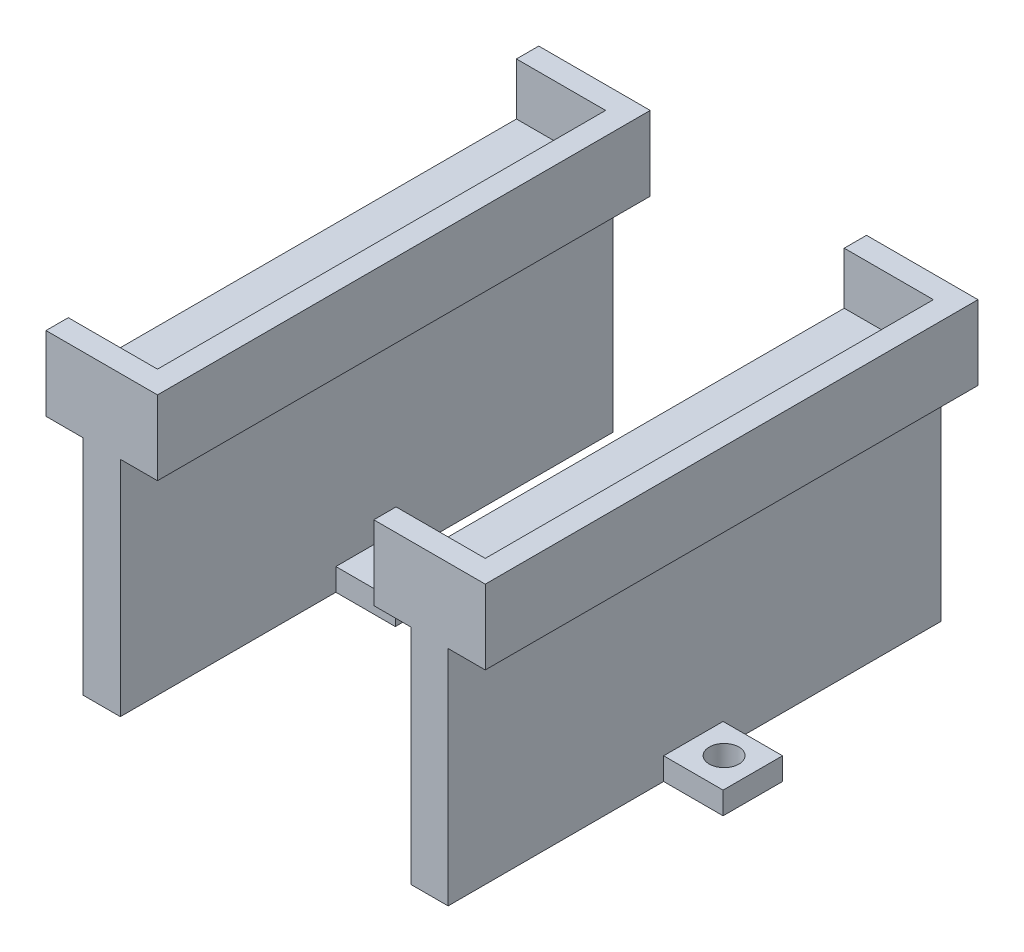
SolidWorks part; units mm, degrees
ref_plane "Front Plane" through (0, 0, 0) normal (0, 0, 1) x (1, 0, 0)
ref_plane "Top Plane" through (0, 0, 0) normal (0, 1, 0) x (1, 0, 0)
ref_plane "Right Plane" through (0, 0, 0) normal (1, 0, 0) x (0, 0, -1)
sketch "Sketch1" plane through (0, 0, 0) normal (0, 1, 0) x (1, 0, 0)
  line L1 (64.0039, -39.1135) -> (-112.9961, -39.1135)
  line L2 (64.0039, -39.1135) -> (64.0039, 27.1865)
  line L3 (64.0039, 27.1865) -> (-112.9961, 27.1865)
  line L4 (-112.9961, -39.1135) -> (-112.9961, 27.1865)
  line L5 (64.0039, -39.1135) -> (-112.9961, 27.1865) construction
  line L6 (64.0039, 27.1865) -> (-112.9961, -39.1135) construction
  point P0 (-24.4961, -5.9635)
  point P5 (0, 0.6131)
extrude "Boss-Extrude1" add sketch "Sketch1" along normal blind 10
sketch "Sketch2" plane through (0, 10, 0) normal (0, 1, 0) x (1, 0, 0)
  line L0 (-112.9961, -39.1135) -> (64.0039, -39.1135) construction
  line L1 (61.0039, -36.1135) -> (-109.9961, -36.1135)
  line L2 (61.0039, -36.1135) -> (61.0039, 24.1865)
  line L3 (61.0039, 24.1865) -> (-109.9961, 24.1865)
  line L4 (-109.9961, -36.1135) -> (-109.9961, 24.1865)
  line L5 (61.0039, -36.1135) -> (-109.9961, 24.1865) construction
  line L6 (61.0039, 24.1865) -> (-109.9961, -36.1135) construction
  line L7 (64.0039, -39.1135) -> (64.0039, 27.1865) construction
  point P0 (-24.4961, -5.9635)
  dimension "D1" = 3
  dimension "D2" = 3
extrude "Cut-Extrude1" cut sketch "Sketch2" against normal blind 7 and the other way through all
sketch "Sketch3" plane through (0, 0, 0) normal (0, -1, 0) x (1, 0, 0)
  line L0 (-112.9961, 39.1135) -> (64.0039, 39.1135) construction
  line L1 (-107.9961, 39.1135) -> (-102.9961, 39.1135)
  line L2 (-107.9961, 39.1135) -> (-107.9961, -27.1865)
  line L3 (-107.9961, -27.1865) -> (-102.9961, -27.1865)
  line L4 (-102.9961, 39.1135) -> (-102.9961, -27.1865)
  line L5 (-107.9961, 39.1135) -> (-102.9961, -27.1865) construction
  line L6 (-107.9961, -27.1865) -> (-102.9961, 39.1135) construction
  line L7 (54.0039, 39.1135) -> (59.0039, 39.1135)
  line L8 (54.0039, 39.1135) -> (54.0039, -27.1865)
  line L9 (54.0039, -27.1865) -> (59.0039, -27.1865)
  line L10 (59.0039, 39.1135) -> (59.0039, -27.1865)
  line L11 (54.0039, 39.1135) -> (59.0039, -27.1865) construction
  line L12 (54.0039, -27.1865) -> (59.0039, 39.1135) construction
  line L13 (64.0039, -27.1865) -> (-112.9961, -27.1865) construction
  line L14 (-112.9961, -27.1865) -> (-112.9961, 39.1135) construction
  line L15 (64.0039, 39.1135) -> (64.0039, -27.1865) construction
  point P0 (-105.4961, 5.9635)
  point P5 (56.5039, 5.9635)
  dimension "D1" = 0
  dimension "D2" = 0
  dimension "D3" = 0
  dimension "D4" = 0
  dimension "D5" = 5
  dimension "D6" = 5
  dimension "D7" = 5
extrude "Boss-Extrude2" add sketch "Sketch3" along normal blind 30
sketch "Sketch4" plane through (0, 0, 0) normal (0, -1, 0) x (1, 0, 0)
  line L0 (-102.9961, 39.1135) -> (54.0039, 39.1135) construction
  line L1 (49.0039, -27.1865) -> (-97.9961, -27.1865)
  line L2 (49.0039, -27.1865) -> (49.0039, 39.1135)
  line L3 (49.0039, 39.1135) -> (-97.9961, 39.1135)
  line L4 (-97.9961, -27.1865) -> (-97.9961, 39.1135)
  line L5 (49.0039, -27.1865) -> (-97.9961, 39.1135) construction
  line L6 (49.0039, 39.1135) -> (-97.9961, -27.1865) construction
  line L7 (54.0039, -27.1865) -> (-102.9961, -27.1865) construction
  line L8 (-102.9961, -27.1865) -> (-102.9961, 39.1135) construction
  line L9 (54.0039, 39.1135) -> (54.0039, -27.1865) construction
  point P0 (-24.4961, 5.9635)
  dimension "D1" = 0
  dimension "D2" = 0
  dimension "D3" = 5
  dimension "D4" = 5
extrude "Cut-Extrude2" cut sketch "Sketch4" against normal blind 30
sketch "Sketch5" plane through (0, -30, 0) normal (0, -1, 0) x (1, 0, 0)
  line L0 (-107.9961, 39.1135) -> (-107.9961, -27.1865) construction
  line L1 (-107.9961, 2.1135) -> (-115.9961, 2.1135)
  line L2 (-107.9961, 2.1135) -> (-107.9961, 10.1135)
  line L3 (-107.9961, 10.1135) -> (-115.9961, 10.1135)
  line L4 (-115.9961, 2.1135) -> (-115.9961, 10.1135)
  line L5 (-107.9961, 2.1135) -> (-115.9961, 10.1135) construction
  line L6 (-107.9961, 10.1135) -> (-115.9961, 2.1135) construction
  line L7 (67.0039, 2.1135) -> (59.0039, 2.1135)
  line L8 (67.0039, 2.1135) -> (67.0039, 10.1135)
  line L9 (67.0039, 10.1135) -> (59.0039, 10.1135)
  line L10 (59.0039, 2.1135) -> (59.0039, 10.1135)
  line L11 (67.0039, 2.1135) -> (59.0039, 10.1135) construction
  line L12 (67.0039, 10.1135) -> (59.0039, 2.1135) construction
  line L13 (59.0039, -27.1865) -> (59.0039, 39.1135) construction
  line L14 (-112.9961, 39.1135) -> (-107.9961, 39.1135) construction
  line L15 (59.0039, 39.1135) -> (64.0039, 39.1135) construction
  circle A0 centre (-111.977, 5.9964) radius 1.8999
  circle A1 centre (63.046, 6.0212) radius 1.9942
  point P0 (-111.9961, 6.1135)
  point P5 (63.0039, 6.1135)
  dimension "D1" = 0
  dimension "D2" = 0
  dimension "D3" = 29
  dimension "D4" = 29
  dimension "D5" = 4
  dimension "D6" = 4
extrude "Boss-Extrude3" add sketch "Sketch5" against normal blind 3
sketch "Sketch6" plane through (0, 0, -27.1865) normal (0, 0, -1) x (-1, 0, 0)
  line L1 (68.5577, 75.1964) -> (121.7583, 75.1964)
  line L2 (68.5577, 75.1964) -> (68.5577, -43.2789)
  line L3 (68.5577, -43.2789) -> (121.7583, -43.2789)
  line L4 (121.7583, 75.1964) -> (121.7583, -43.2789)
  line L5 (68.5577, 75.1964) -> (121.7583, -43.2789) construction
  line L6 (68.5577, -43.2789) -> (121.7583, 75.1964) construction
  point P0 (95.158, 15.9587)
extrude "Cut-Extrude3" cut sketch "Sketch6" against normal through all
move or copy body "Body-Move/Copy1" bodies to move or copy 107 copy yes number of copies 1 translate (44.1041, 0, 0) parameters "D1"=44.1041, "D2"=0, "D3"=0
